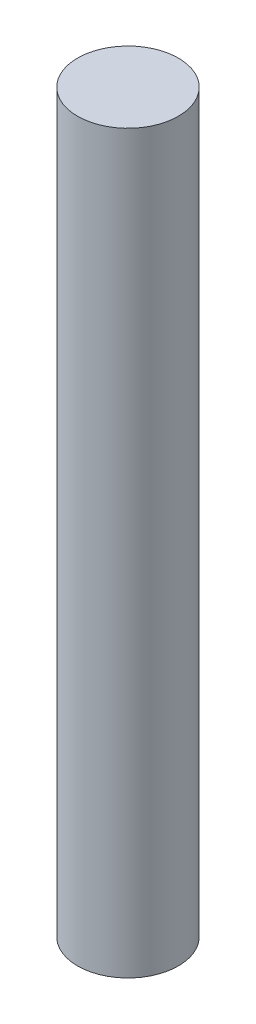
SolidWorks part; units mm, degrees
ref_plane "Front Plane" through (0, 0, 0) normal (0, 0, 1) x (1, 0, 0)
ref_plane "Top Plane" through (0, 0, 0) normal (0, 1, 0) x (1, 0, 0)
ref_plane "Right Plane" through (0, 0, 0) normal (1, 0, 0) x (0, 0, -1)
sketch "Sketch1" plane through (0, 0, 0) normal (0, 1, 0) x (1, 0, 0)
  circle A0 centre (0, 0) radius 0.5
  dimension "D1" = 1
extrude "Boss-Extrude1" add sketch "Sketch1" along normal blind 7.3
